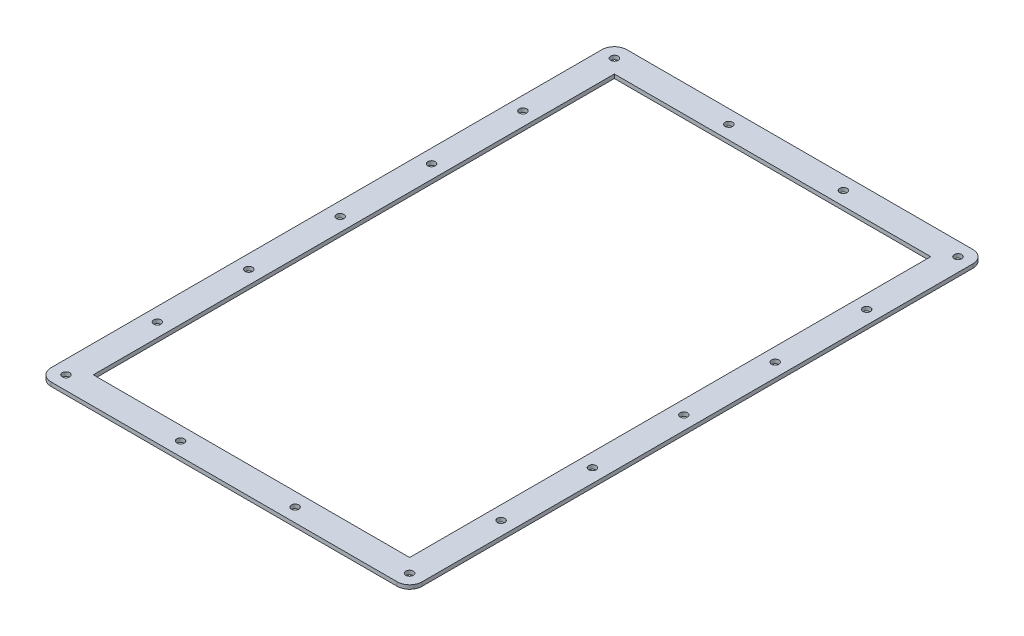
SolidWorks part; units mm, degrees
material "5052-H32"
ref_plane "Front Plane" through (0, 0, 0) normal (0, 0, 1) x (1, 0, 0)
ref_plane "Top Plane" through (0, 0, 0) normal (0, 1, 0) x (1, 0, 0)
ref_plane "Right Plane" through (0, 0, 0) normal (1, 0, 0) x (0, 0, -1)
sketch "Sketch1" plane through (0, 0, 0) normal (0, 1, 0) x (1, 0, 0)
  line L0 (-147, 192) -> (152, 192)
  line L1 (-125, -250) -> (130, -250)
  line L2 (-125, -250) -> (-125, 170)
  line L3 (-125, 170) -> (130, 170)
  line L4 (130, -250) -> (130, 170)
  line L5 (-125, -250) -> (130, 170) construction
  line L6 (-125, 170) -> (130, -250) construction
  line L7 (152, -272) -> (152, 192)
  line L8 (-147, -272) -> (152, -272)
  line L9 (-147, -272) -> (-147, 192)
  line L12 (130, -40) -> (-125, -40) construction
  circle A34 centre (141, 181) radius 3
  circle A35 centre (48.6667, 181) radius 3
  circle A36 centre (-43.6667, 181) radius 3
  circle A37 centre (-136, 181) radius 3
  circle A90 centre (141, 107.3333) radius 3
  circle A91 centre (141, 33.6667) radius 3
  circle A92 centre (141, -40) radius 3
  circle A93 centre (141, -113.6667) radius 3
  circle A94 centre (141, -187.3333) radius 3
  circle A102 centre (-136, 107.3333) radius 3
  circle A103 centre (141, -261) radius 3
  circle A106 centre (-136, 33.6667) radius 3
  circle A107 centre (48.6667, -261) radius 3
  circle A110 centre (-136, -40) radius 3
  circle A111 centre (-43.6667, -261) radius 3
  circle A114 centre (-136, -113.6667) radius 3
  circle A115 centre (-136, -261) radius 3
  circle A118 centre (-136, -187.3333) radius 3
  circle A119 centre (48.6667, -113.6667) radius 3 [skipped]
  circle A120 centre (-43.6667, -113.6667) radius 3 [skipped]
  circle A121 centre (48.6667, 107.3333) radius 3 [skipped]
  circle A122 centre (-43.6667, 107.3333) radius 3 [skipped]
  circle A123 centre (48.6667, 33.6667) radius 3 [skipped]
  circle A124 centre (48.6667, -40) radius 3 [skipped]
  circle A125 centre (-43.6667, -40) radius 3 [skipped]
  circle A126 centre (-43.6667, 33.6667) radius 3 [skipped]
  circle A127 centre (48.6667, -187.3333) radius 3 [skipped]
  circle A128 centre (-43.6667, -187.3333) radius 3 [skipped]
  dimension "D4" = 6
  dimension "D2" = 420
  dimension "D1" = 22
  dimension "D3" = 255
  dimension "D5" = 11
  dimension "D6" = 11
  dimension "D9" = 73.6667
  dimension "D10" = 92.3333
  dimension "D7" = 4
  dimension "D8" = 7
extrude "Boss-Extrude1" add sketch "Sketch1" along normal blind 3.175
fillet "Fillet1" radius 10 4 edges at (152, 1.5875, 272) (-147, 1.5875, 272) (152, 1.5875, -192) (-147, 1.5875, -192)
equation "\"L\"= 420mm"
equation "\"W\"= 255mm"
equation "\"H\"= 110mm"
equation "\"Compartment Width\"= 80"
equation "\"T\"= 4.7625 * 2 / 3mm"
equation "\"Inside Fillet Radius\"= 5.55625mm"
equation "\"Hole\"=25mm"
equation "\"D2@Sketch1\"=\"L\""
equation "\"D1@Boss-Extrude1\"=\"T\""
equation "\"D3@Sketch1\"=\"W\""
equation "\"D9@Sketch1\"=(\"L\"+22)/6"
equation "\"D10@Sketch1\"=(\"W\"+22)/3"
equation "\"Offset\"= 16mm"
equation "\"Wheel to Wall\"= 43"
